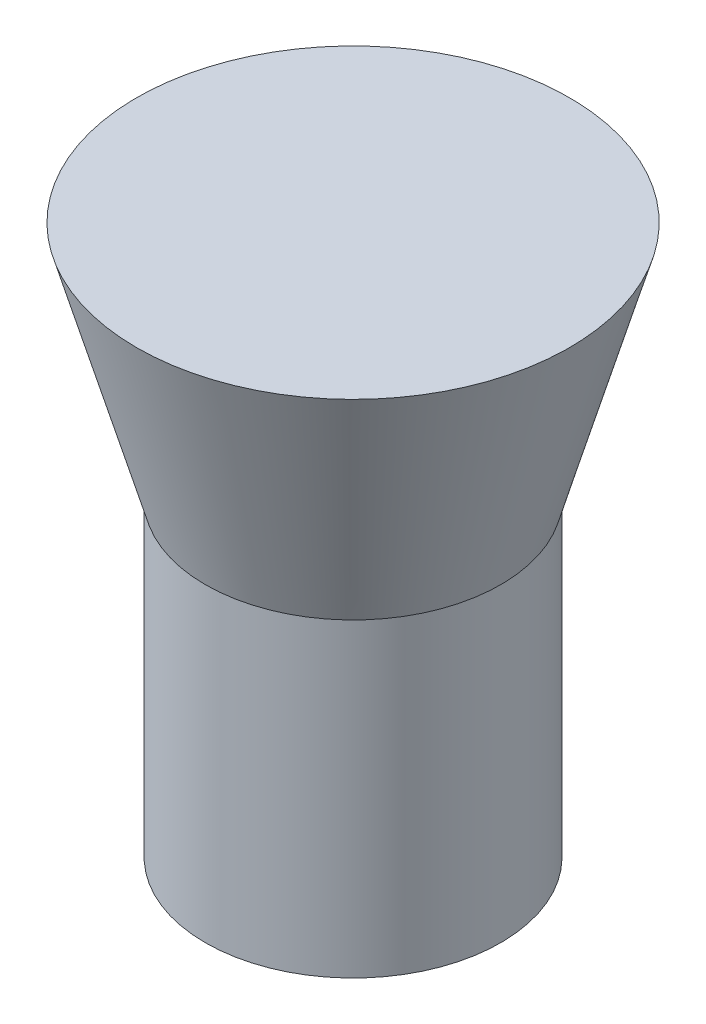
SolidWorks part; units mm, degrees
ref_plane "Front Plane" through (0, 0, 0) normal (0, 0, 1) x (1, 0, 0)
ref_plane "Top Plane" through (0, 0, 0) normal (0, 1, 0) x (1, 0, 0)
ref_plane "Right Plane" through (0, 0, 0) normal (1, 0, 0) x (0, 0, -1)
sketch "Sketch1" plane through (0, 0, 0) normal (0, 1, 0) x (1, 0, 0)
  circle A0 centre (0, 0) radius 2.15
  dimension "D1" = 4.3
extrude "Boss-Extrude1" add sketch "Sketch1" along normal blind 8
sketch "Sketch2" plane through (0, 8, 0) normal (0, 1, 0) x (1, 0, 0)
  circle A0 centre (0, 0) radius 3.15
  circle A1 centre (0, 0) radius 2.15 construction
  dimension "D1" = 1
extrude "Boss-Extrude2" add sketch "Sketch2" against normal blind 4.5 draft 16
